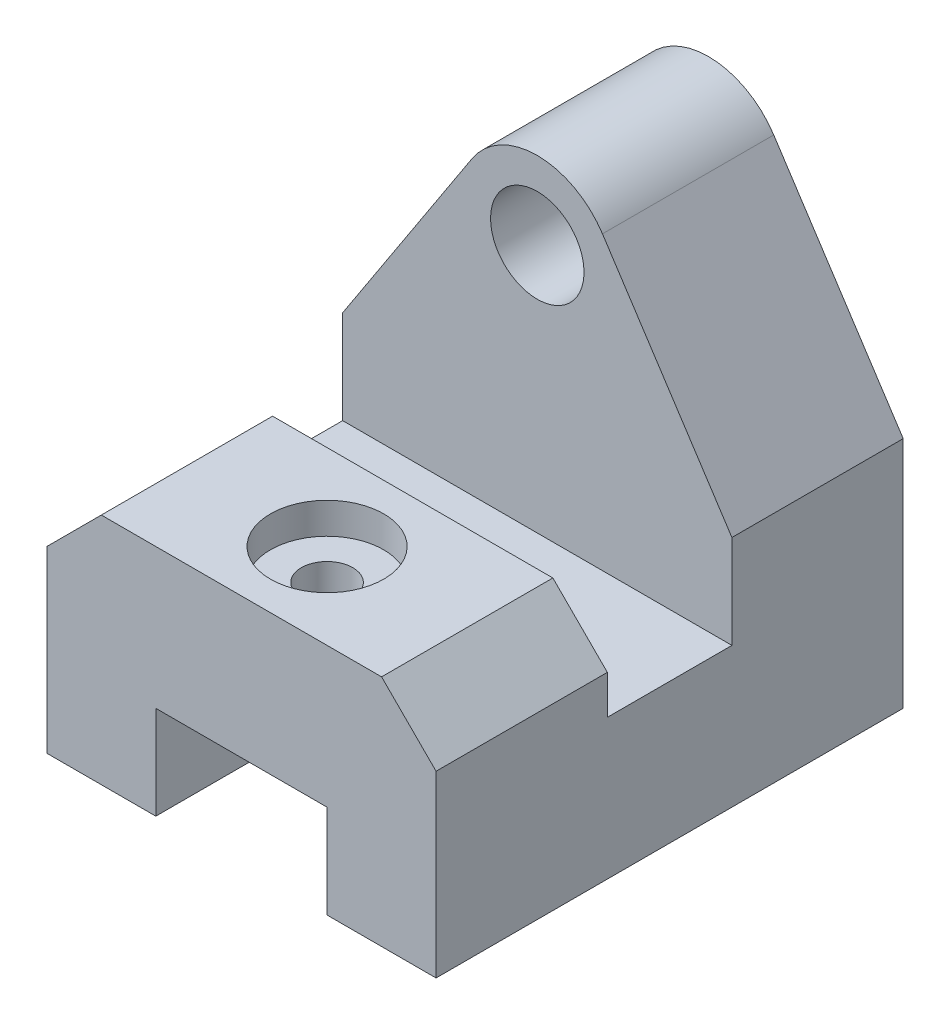
SolidWorks part; units mm, degrees
ref_plane "Front Plane" through (0, 0, 0) normal (0, 0, 1) x (1, 0, 0)
ref_plane "Top Plane" through (0, 0, 0) normal (0, 1, 0) x (1, 0, 0)
ref_plane "Right Plane" through (0, 0, 0) normal (1, 0, 0) x (0, 0, -1)
sketch "Sketch1" plane through (0, 0, 0) normal (0, 0, 1) x (1, 0, 0)
  line L1 (0, 0) -> (50, 0)
  line L2 (0, 0) -> (0, 30)
  line L3 (0, 30) -> (50, 30)
  line L4 (50, 0) -> (50, 30)
  dimension "D1" = 30
  dimension "D2" = 50
extrude "Boss-Extrude1" add sketch "Sketch1" against normal blind 60
sketch "Sketch2" plane through (0, 0, -60) normal (0, 0, -1) x (-1, 0, 0)
  line L0 (-50, 30) -> (0, 30) construction
  line L1 (-50, 30) -> (-33.3734, 55.4668)
  line L2 (0, 30) -> (-16.6266, 55.4668)
  line L3 (-50, 30) -> (0, 30)
  arc A0 (-16.6266, 55.4668) -> (-33.3734, 55.4668) centre (-25, 50) ccw
  circle A1 centre (-25, 50) radius 6
  point P11 (-25, 30)
  dimension "D1" = 20
  dimension "D3" = 12
  dimension "D2" = 20
extrude "Boss-Extrude2" add sketch "Sketch2" against normal blind 22 contours L3 L2 A0 L1 | A1
cosmetic thread "Cosmetic Thread4" parameters "D2"=14
sketch "Sketch3" plane through (50, 0, 0) normal (1, 0, 0) x (0, 0, -1)
  line L1 (38, 30) -> (22, 30)
  line L2 (38, 30) -> (38, 18)
  line L3 (38, 18) -> (22, 18)
  line L4 (22, 30) -> (22, 18)
  dimension "D1" = 12
  dimension "D2" = 16
extrude "Cut-Extrude1" cut sketch "Sketch3" against normal through all
sketch "Sketch4" plane through (0, 0, 0) normal (0, 0, 1) x (1, 0, 0)
  line L0 (0, 0) -> (50, 0) construction
  line L1 (14, 0) -> (36, 0)
  line L2 (14, 0) -> (14, 12)
  line L3 (14, 12) -> (36, 12)
  line L4 (36, 0) -> (36, 12)
  arc A0 (33.3734, 55.4668) -> (16.6266, 55.4668) centre (25, 50) ccw construction
  point P6 (25, 12)
  point P10 (25, 60)
  dimension "D1" = 12
  dimension "D2" = 22
extrude "Cut-Extrude2" cut sketch "Sketch4" against normal through all
sketch "Sketch5" plane through (0, 0, 0) normal (0, 0, 1) x (1, 0, 0)
  line L0 (50, 30) -> (50, 23)
  line L1 (50, 0) -> (50, 30) construction
  line L2 (50, 23) -> (43, 30)
  line L3 (50, 30) -> (0, 30) construction
  line L4 (43, 30) -> (50, 30)
  line L5 (0, 23) -> (0, 30)
  line L6 (0, 30) -> (0, 0) construction
  line L7 (0, 30) -> (7, 30)
  line L8 (7, 30) -> (0, 23)
  dimension "D1" = 7
  dimension "D2" = 7
  dimension "D3" = 7
  dimension "D4" = 7
extrude "Cut-Extrude3" cut sketch "Sketch5" against normal up to next
hole_wizard "CBORE for M6 Hex Head Bolt2" positions "Sketch11" profile "Sketch10" counterbore size "M6" standard "ISO" end condition through all
sketch "Sketch11" plane through (0, 30, 0) normal (0, 1, 0) x (1, 0, 0)
  line L0 (43, 0) -> (7, 0) construction
  line L1 (43, 22) -> (43, 0) construction
  point P0 (25, 11)
  dimension "D1" = 11
  dimension "D2" = 18
sketch "Sketch10" plane through (25, 30, -11) normal (1, 0, 0) x (0, 0, 1)
  line L0 (0, 0) -> (0, 30)
  line L1 (0, 30) -> (3.3, 30)
  line L3 (3.3, 30) -> (3.3, 4)
  line L4 (3.3, 4) -> (7.2735, 4)
  line L5 (7.2735, 4) -> (7.2735, 0)
  line L7 (7.2735, 0) -> (0, 0)
  line L11 (0, -6.35) -> (0, 107.95) construction
  dimension "Thru Hole Dia." = 6.6
  dimension "Thru Hole Depth" = 30
  dimension "C'Bore Dia." = 14.547
  dimension "C'Bore Depth" = 4
